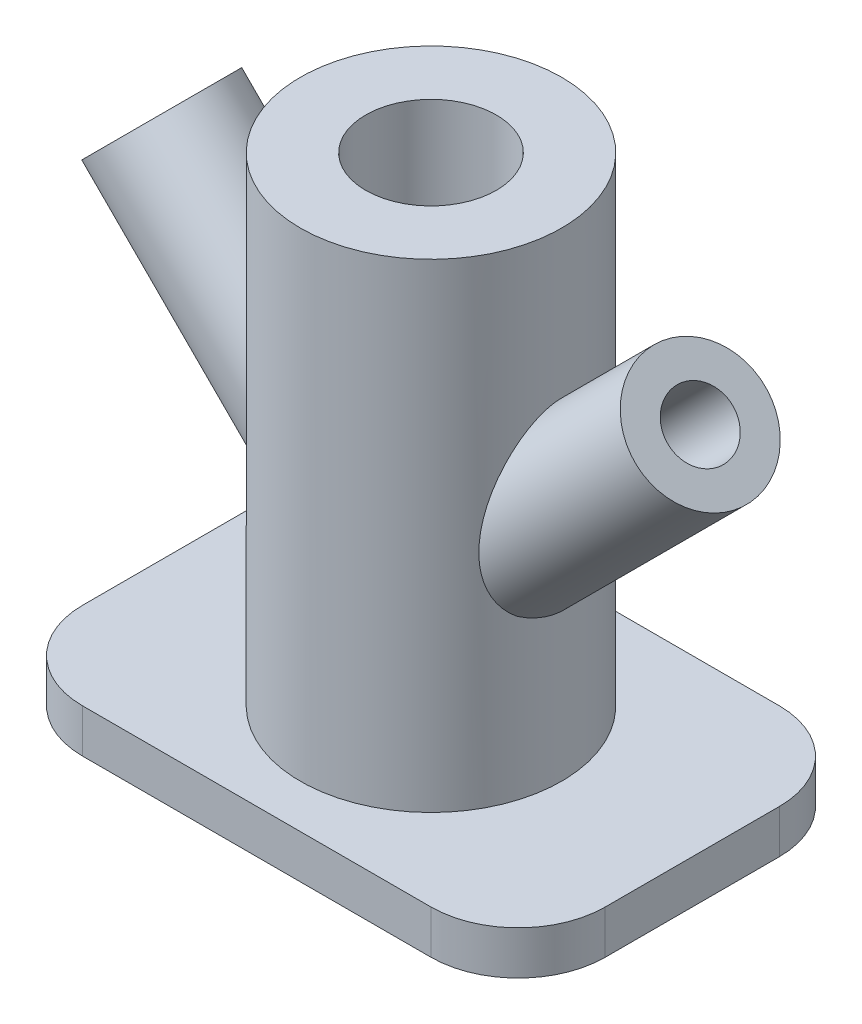
SolidWorks part; units mm, degrees
ref_plane "Alzado" through (0, 0, 0) normal (0, 0, 1) x (1, 0, 0)
ref_plane "Planta" through (0, 0, 0) normal (0, 1, 0) x (1, 0, 0)
ref_plane "Vista lateral" through (0, 0, 0) normal (1, 0, 0) x (0, 0, -1)
sketch "Croquis1" plane through (0, 0, 0) normal (0, 1, 0) x (1, 0, 0)
  line L1 (-60, -40) -> (60, -40)
  line L2 (-60, -40) -> (-60, 40)
  line L3 (-60, 40) -> (60, 40)
  line L4 (60, -40) -> (60, 40)
  line L5 (-60, -40) -> (60, 40) construction
  line L6 (-60, 40) -> (60, -40) construction
  point P0 (0, 0)
extrude "Saliente-Extruir1" add sketch "Croquis1" along normal blind 10
fillet "Redondeo1" radius 20 4 edges at (-60, 5, -40) (60, 5, -40) (-60, 5, 40) (60, 5, 40)
sketch "Croquis2" plane through (0, 0, 0) normal (0, 1, 0) x (1, 0, 0)
  circle A0 centre (0, 0) radius 30
extrude "Saliente-Extruir3" add sketch "Croquis2" along normal blind 120
sketch "Croquis5" plane through (0, 0, 0) normal (0, 0, 1) x (1, 0, 0)
  line L0 (30, 65) -> (61.8198, 96.8198) construction
  line L1 (30, 10) -> (30, 120) construction
  line L2 (-30, 65) -> (-61.8198, 96.8198) construction
  line L3 (-30, 120) -> (-30, 10) construction
  line L4 (45.7168, 112.9228) -> (61.8198, 96.8198) construction
  line L5 (61.8198, 96.8198) -> (81.3549, 77.2847) construction
  line L6 (-61.8198, 96.8198) -> (-47.3612, 111.2784) construction
  line L7 (-47.3612, 111.2784) -> (-77.7297, 80.9099) construction
ref_plane "Plano1" through (79.3198, 79.3198, 0) normal (0.7071, 0.7071, 0) x (0, 0, -1)
ref_plane "Plano3" through (-79.3198, 79.3198, 0) normal (-0.7071, 0.7071, 0) x (0.7071, 0.7071, 0)
sketch "Croquis6" plane through (79.3198, 79.3198, 0) normal (0.7071, 0.7071, 0) x (0, 0, -1)
  circle A0 centre (0, 24.7487) radius 15
extrude "Saliente-Extruir4" add sketch "Croquis6" against normal blind 59
sketch "Croquis7" plane through (79.3198, 79.3198, 0) normal (0.7071, 0.7071, 0) x (0, 0, -1)
  circle A0 centre (0, 24.7487) radius 7.5
extrude "Cortar-Extruir1" cut sketch "Croquis7" against normal blind 64
sketch "Croquis8" plane through (0, 120, 0) normal (0, 1, 0) x (1, 0, 0)
  circle A0 centre (0, 0) radius 15
extrude "Cortar-Extruir2" cut sketch "Croquis8" against normal blind 150
sketch "Croquis9" plane through (79.3198, 79.3198, 0) normal (0.7071, 0.7071, 0) x (0, 0, -1)
  circle A0 centre (0, 24.7487) radius 7.5
extrude "Cortar-Extruir3" cut sketch "Croquis9" against normal blind 83
sketch "Croquis10" plane through (-79.3198, 79.3198, 0) normal (-0.7071, 0.7071, 0) x (0.7071, 0.7071, 0)
  circle A0 centre (24.7487, 0) radius 15
extrude "Saliente-Extruir5" add sketch "Croquis10" against normal blind 61
sketch "Croquis11" plane through (-79.3198, 79.3198, 0) normal (-0.7071, 0.7071, 0) x (0.7071, 0.7071, 0)
  line L0 (24.7487, 0) -> (45.1963, 0) construction
  circle A0 centre (24.7487, 0) radius 7.5
extrude "Cortar-Extruir4" cut sketch "Croquis11" against normal blind 78
sketch "Croquis12" plane through (0, 120, 0) normal (0, 1, 0) x (1, 0, 0)
  circle A0 centre (0, 0) radius 15
extrude "Cortar-Extruir5" cut sketch "Croquis12" against normal blind 134
